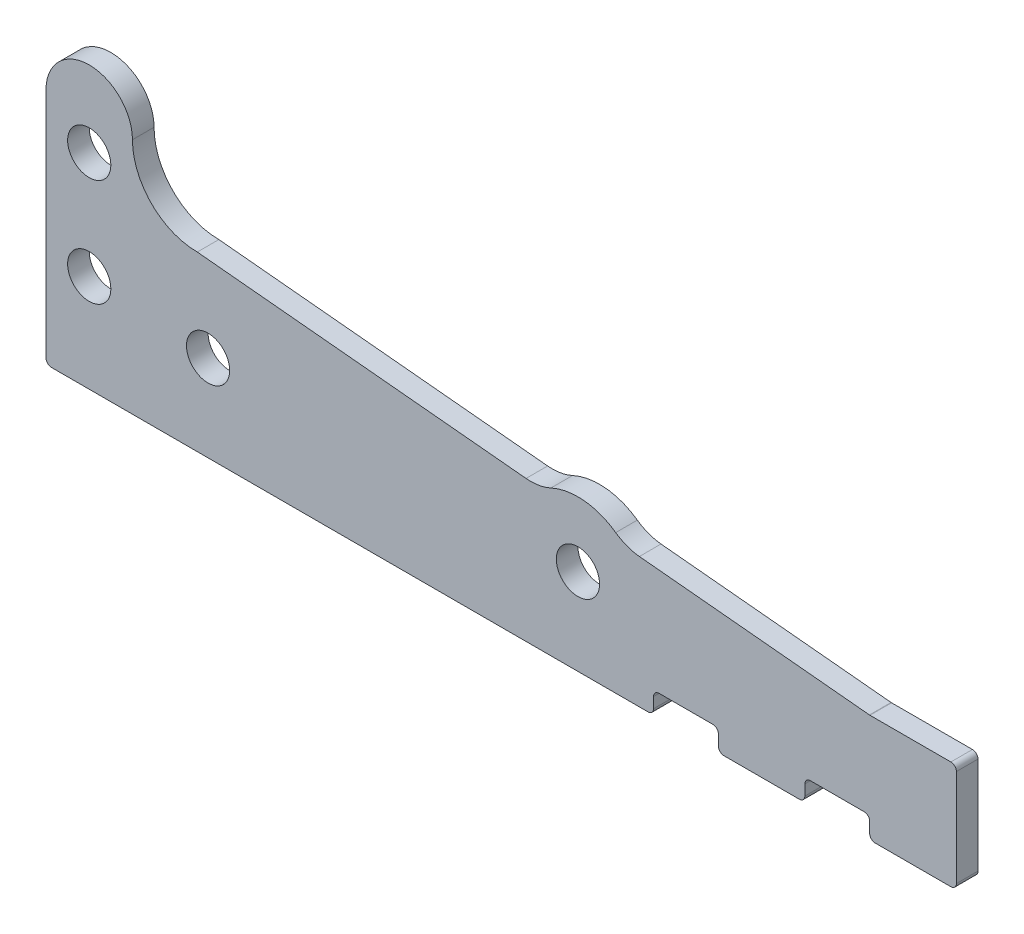
SolidWorks part; units mm, degrees
ref_plane "Front Plane" through (0, 0, 0) normal (0, 0, 1) x (1, 0, 0)
ref_plane "Top Plane" through (0, 0, 0) normal (0, 1, 0) x (1, 0, 0)
ref_plane "Right Plane" through (0, 0, 0) normal (1, 0, 0) x (0, 0, -1)
sketch "Sketch1" plane through (0, 0, 0) normal (0, 0, 1) x (1, 0, 0)
  line L0 (3.175, 19.05) -> (3.175, 0) construction
  line L1 (0, 0) -> (6.35, 0) construction
  line L2 (0, 0) -> (0, 19.05)
  line L3 (0, 19.05) -> (6.35, 19.05)
  line L4 (6.35, 0) -> (6.35, 19.05) construction
  line L5 (3.175, 13.462) -> (3.175, 5.588) construction
  line L6 (6.35, 0) -> (60.5079, 0) construction
  line L9 (0, 0) -> (0, -1.5875)
  line L11 (60.5079, -1.5875) -> (60.5079, 0)
  line L12 (0, 19.05) -> (-1.5875, 19.05) construction
  line L13 (-1.5875, 19.05) -> (-1.5875, -1.5875) construction
  line L14 (-1.5875, -1.5875) -> (0, -1.5875) construction
  line L15 (60.5079, 11.1125) -> (6.35, 11.1125) construction
  line L16 (60.5079, 0) -> (60.5079, 11.1125) construction
  line L17 (11.1125, 11.1125) -> (60.5079, 6.35)
  line L18 (60.5079, 6.35) -> (60.5079, 0)
  line L19 (60.5079, 6.35) -> (66.8767, 6.35)
  line L20 (66.8767, 6.35) -> (66.8767, -1.5875)
  line L21 (66.8767, -1.5875) -> (60.5079, -1.5875)
  line L22 (60.5079, 0) -> (55.7454, 0)
  line L23 (55.7454, 0) -> (55.7454, -1.5875)
  line L24 (55.7454, -1.5875) -> (49.3954, -1.5875)
  line L25 (49.3954, -1.5875) -> (49.3954, 0)
  line L26 (49.3954, 0) -> (44.6329, 0)
  line L27 (44.6329, 0) -> (44.6329, -1.5875)
  line L28 (44.6329, -1.5875) -> (0, -1.5875)
  line L29 (11.9062, -1.5875) -> (11.9062, 4.7625) construction
  line L30 (39.0767, -1.5875) -> (39.0767, 4.7625) construction
  circle A0 centre (3.175, 13.462) radius 1.5875
  circle A1 centre (3.175, 5.588) radius 1.5875
  circle A2 centre (3.175, 15.875) radius 3.175
  circle A3 centre (3.175, 3.175) radius 3.175
  circle A4 centre (11.1125, 15.875) radius 4.7625
  circle A5 centre (11.9062, 4.7625) radius 1.5875
  circle A6 centre (39.0767, 4.7625) radius 1.5875
  circle A7 centre (39.0767, 4.7625) radius 4.7625
  point P11 (3.175, 9.525)
  point P12 (3.175, 9.525)
  point P30 (6.35, 15.875)
  dimension "D1" = 19.05
  dimension "D2" = 3.175
  dimension "D8" = 11.1125
  dimension "D9" = 6.35
  dimension "D10" = 6.3688
  dimension "D13" = 6.35
  dimension "D3" = 6.35
  dimension "D4" = 7.874
  dimension "D5" = 1.5875
  dimension "D6" = 62.0954
  dimension "D7" = 1.5875
  dimension "D11" = 15.875
  dimension "D12" = 6.35
  dimension "D14" = 5.5562
  dimension "D15" = 5.5562
extrude "Boss-Extrude1" add sketch "Sketch1" along normal blind 1.5875
fillet "Fillet1" radius 0.4064 12 edges at (66.8767, 6.35, 0.7937) (60.5079, 6.35, 0.7937) (55.7454, 0, 0.7937) (44.6329, 0, 0.7937) (44.6329, -1.5875, 0.7937) (55.7454, -1.5875, 0.7937) (66.8767, -1.5875, 0.7937) (60.5079, 0, 0.7937) (60.5079, -1.5875, 0.7937) (49.3954, 0, 0.7937) (49.3954, -1.5875, 0.7937) (0, -1.5875, 0.7937)
fillet "Fillet2" radius 3.5719 2 edges at (36.3651, 8.6777, 0.7937) (42.4862, 8.0876, 0.7937)
